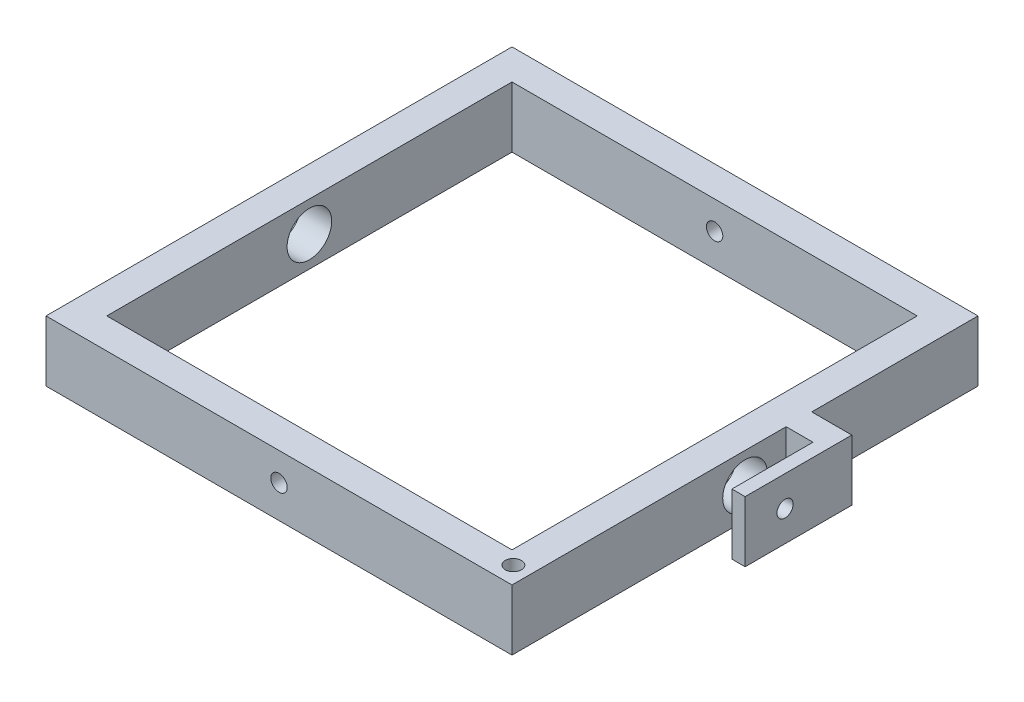
SolidWorks part; units mm, degrees
ref_plane "Front Plane" through (0, 0, 0) normal (0, 0, 1) x (1, 0, 0)
ref_plane "Top Plane" through (0, 0, 0) normal (0, 1, 0) x (1, 0, 0)
ref_plane "Right Plane" through (0, 0, 0) normal (1, 0, 0) x (0, 0, -1)
sketch "Sketch1" plane through (0, 0, 0) normal (0, 1, 0) x (1, 0, 0)
  line L1 (-100, -100) -> (100, -100)
  line L2 (-100, -100) -> (-100, 100)
  line L3 (-100, 100) -> (100, 100)
  line L4 (100, -100) -> (100, 100)
  line L5 (-100, -100) -> (100, 100) construction
  line L6 (-100, 100) -> (100, -100) construction
  line L7 (-115, -115) -> (115, -115)
  line L8 (-115, -115) -> (-115, 115)
  line L9 (-115, 115) -> (115, 115)
  line L10 (115, -115) -> (115, 115)
  line L11 (-115, -115) -> (115, 115) construction
  line L12 (-115, 115) -> (115, -115) construction
  point P0 (0, 0)
  point P6 (0, 0)
extrude "Boss-Extrude1" add sketch "Sketch1" along normal blind 30
sketch "Sketch2" plane through (115, 0, 0) normal (1, 0, 0) x (0, 0, -1)
  circle A0 centre (0, 15) radius 11
extrude "Cut-Extrude3" cut sketch "Sketch2" against normal blind 206
sketch "Sketch3" plane through (115, 0, 0) normal (1, 0, 0) x (0, 0, -1)
  line L0 (-115, 0) -> (115, 0) construction
  line L1 (20.2866, 0) -> (32.935, 0)
  line L2 (20.2866, 0) -> (20.2866, 30)
  line L3 (20.2866, 30) -> (32.935, 30)
  line L4 (32.935, 0) -> (32.935, 30)
  line L5 (-115, 30) -> (115, 30) construction
extrude "Boss-Extrude2" add sketch "Sketch3" along normal blind 28
sketch "Sketch4" plane through (0, 0, -20.2866) normal (0, 0, 1) x (1, 0, 0)
  line L0 (143, 0) -> (115, 0) construction
  line L1 (143, 30) -> (109.723, 30)
  line L2 (143, 30) -> (143, 0)
  line L3 (143, 0) -> (109.723, 0)
  line L4 (109.723, 30) -> (109.723, 0)
extrude "Boss-Extrude4" add sketch "Sketch4" along normal blind 41
sketch "Sketch6" plane through (-115, 0, 0) normal (-1, 0, 0) x (0, 0, 1)
  circle A0 centre (0, 15) radius 4
extrude "Cut-Extrude4" cut sketch "Sketch6" against normal blind 218
sketch "Sketch8" plane through (0, 0, 115) normal (0, 0, 1) x (1, 0, 0)
  circle A0 centre (0, 16.1759) radius 4.0467
extrude "Cut-Extrude6" cut sketch "Sketch8" against normal blind 280
sketch "Sketch9" plane through (-115, 0, 0) normal (-1, 0, 0) x (0, 0, 1)
  circle A0 centre (0, 15) radius 11
extrude "Cut-Extrude7" cut sketch "Sketch9" against normal blind 230
sketch "Sketch11" plane through (0, 0, 20.7134) normal (0, 0, 1) x (1, 0, 0)
  line L0 (115, 0) -> (143, 0) construction
  line L1 (115, 30) -> (134.7762, 30)
  line L2 (115, 30) -> (115, 0)
  line L3 (115, 0) -> (134.7762, 0)
  line L4 (134.7762, 30) -> (134.7762, 0)
extrude "Cut-Extrude8" cut sketch "Sketch11" against normal blind 41
sketch "Sketch12" plane through (-115, 0, 0) normal (-1, 0, 0) x (0, 0, 1)
  circle A0 centre (0, 15) radius 4
extrude "Cut-Extrude9" cut sketch "Sketch12" against normal blind 264
sketch "Sketch13" plane through (0, 30, 0) normal (0, 1, 0) x (1, 0, 0)
  circle A0 centre (106.8511, -106.1772) radius 4
extrude "Cut-Extrude10" cut sketch "Sketch13" against normal blind 264
sketch "Sketch15" plane through (0, 0, 20.7134) normal (0, 0, 1) x (1, 0, 0)
  line L1 (143, 30) -> (134.7762, 30)
  line L2 (143, 30) -> (143, 0)
  line L3 (143, 0) -> (134.7762, 0)
  line L4 (134.7762, 30) -> (134.7762, 0)
extrude "Cut-Extrude11" cut sketch "Sketch15" against normal blind 64
sketch "Sketch16" plane through (0, 0, -20.2866) normal (0, 0, 1) x (1, 0, 0)
  line L0 (115, 0) -> (134.7762, 0) construction
  line L1 (134.7762, 30) -> (128.2637, 30)
  line L2 (134.7762, 30) -> (134.7762, 0)
  line L3 (134.7762, 0) -> (128.2637, 0)
  line L4 (128.2637, 30) -> (128.2637, 0)
extrude "Boss-Extrude5" add sketch "Sketch16" along normal blind 40
sketch "Sketch17" plane through (-115, 0, 0) normal (-1, 0, 0) x (0, 0, 1)
  circle A0 centre (0, 15) radius 4
extrude "Cut-Extrude12" cut sketch "Sketch17" against normal blind 276
